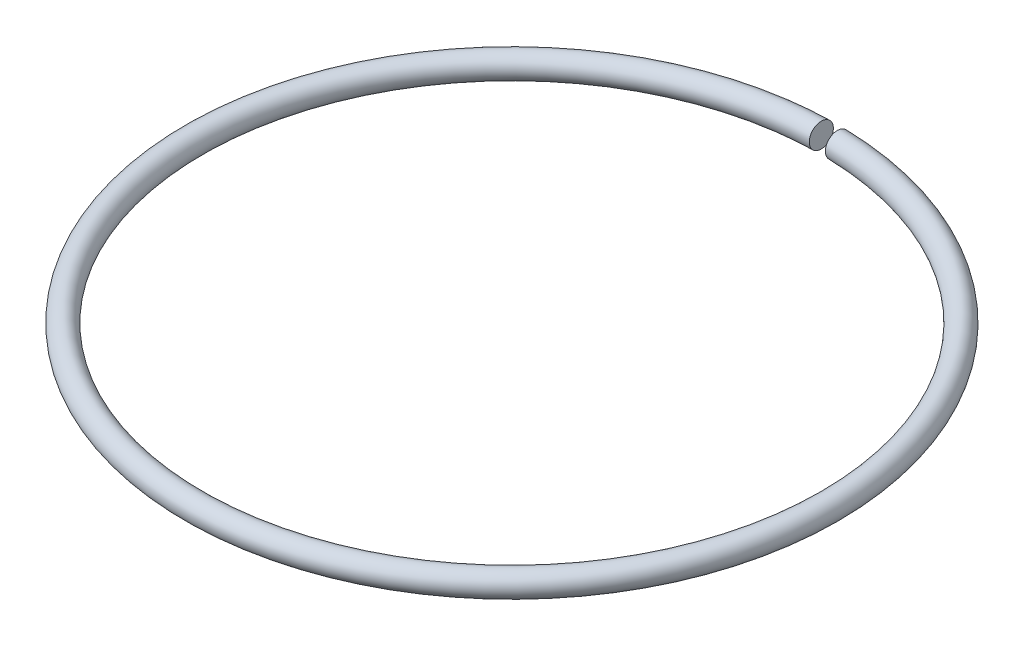
SolidWorks part; units mm, degrees
ref_plane "Plano frontal" through (0, 0, 0) normal (0, 0, 1) x (1, 0, 0)
ref_plane "Plano superior" through (0, 0, 0) normal (0, 1, 0) x (1, 0, 0)
ref_plane "Plano direito" through (0, 0, 0) normal (1, 0, 0) x (0, 0, -1)
sketch "Esboço1" plane through (0, 0, 0) normal (0, 0, 1) x (1, 0, 0)
  line L0 (0, 0) -> (0, 15.1332) construction
  circle A0 centre (39.5, 0) radius 1.5
  dimension "D1" = 3
  dimension "D2" = 39.5
revolve "Revolução1" add sketch "Esboço1" angle 360 about L0
sketch "Esboço2" plane through (0, 0, 0) normal (0, 1, 0) x (1, 0, 0)
  line L0 (0, 0) -> (0, 36.2503) construction
  line L1 (-1, 42.8091) -> (1, 42.8091)
  line L2 (-1, 42.8091) -> (-1, 36.2503)
  line L3 (-1, 36.2503) -> (1, 36.2503)
  line L4 (1, 42.8091) -> (1, 36.2503)
  dimension "D1" = 2
extrude "Corte-extrusão1" cut sketch "Esboço2" against normal through all both and the other way through all
